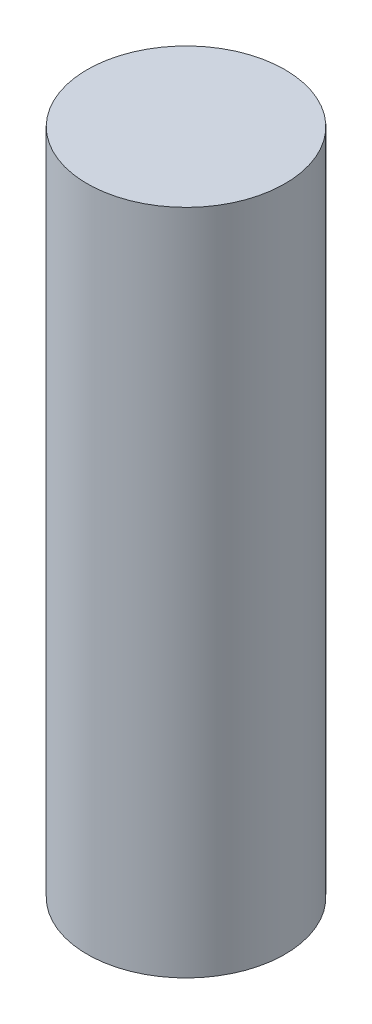
SolidWorks part; units mm, degrees
ref_plane "Front Plane" through (0, 0, 0) normal (0, 0, 1) x (1, 0, 0)
ref_plane "Top Plane" through (0, 0, 0) normal (0, 1, 0) x (1, 0, 0)
ref_plane "Right Plane" through (0, 0, 0) normal (1, 0, 0) x (0, 0, -1)
sketch "Sketch3" plane through (0, 0, 0) normal (0, 0, 1) x (1, 0, 0)
  line L0 (0, -2658.3561) -> (0, 2658.3561) construction
  line L1 (-3000, 0) -> (3000, 0) construction
  line L3 (0, 0) -> (2000, 0)
  line L4 (0, 0) -> (0, 13500)
  line L5 (0, 13500) -> (2000, 13500)
  line L6 (2000, 0) -> (2000, 13500)
  point P4 (0, 0)
  point P8 (0, 0)
  dimension "D1" = 13500
  dimension "D2" = 5316.7123
  dimension "D3" = 6000
  dimension "D4" = 2000
revolve "Revolve1" add sketch "Sketch3" angle 360 about L0
